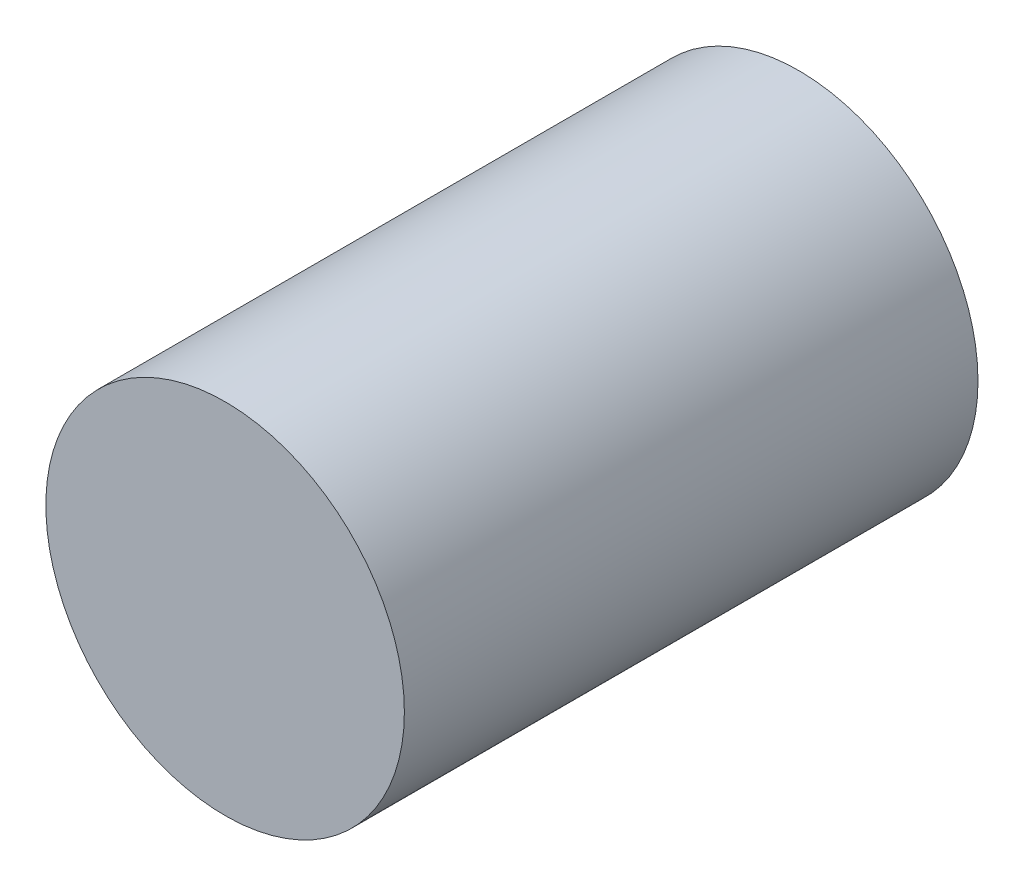
SolidWorks part; units mm, degrees
ref_plane "Alzado" through (0, 0, 0) normal (0, 0, 1) x (1, 0, 0)
ref_plane "Planta" through (0, 0, 0) normal (0, 1, 0) x (1, 0, 0)
ref_plane "Vista lateral" through (0, 0, 0) normal (1, 0, 0) x (0, 0, -1)
sketch "Croquis1" plane through (0, 0, 0) normal (0, 0, 1) x (1, 0, 0)
  circle A0 centre (0, 0) radius 7.5
  dimension "D1" = 15
extrude "Saliente-Extruir1" add sketch "Croquis1" along normal blind 24
